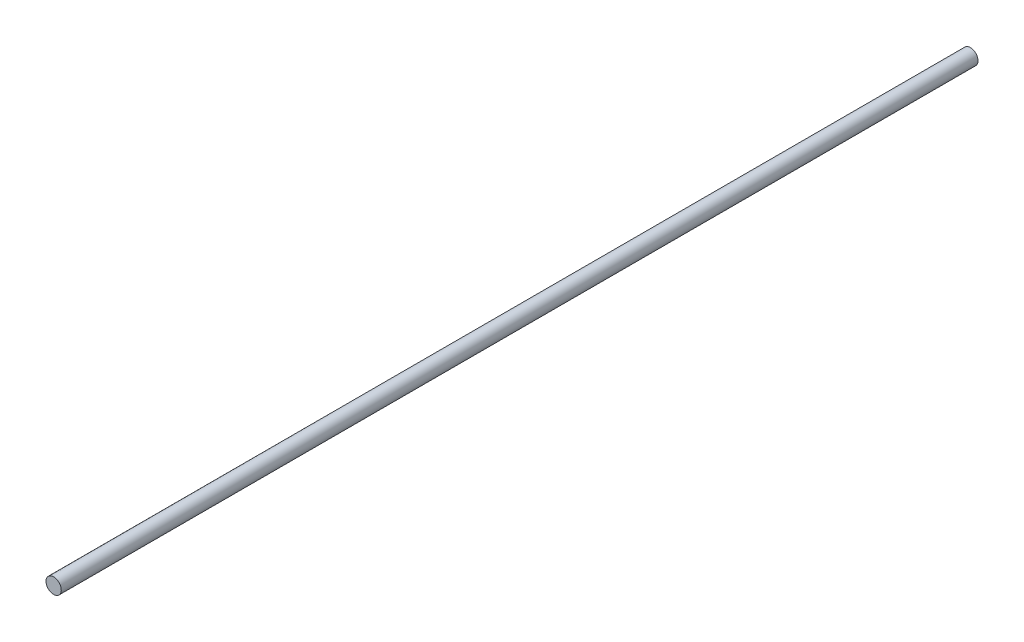
SolidWorks part; units mm, degrees
ref_plane "前视基准面" through (0, 0, 0) normal (0, 0, 1) x (1, 0, 0)
ref_plane "上视基准面" through (0, 0, 0) normal (0, 1, 0) x (1, 0, 0)
ref_plane "右视基准面" through (0, 0, 0) normal (1, 0, 0) x (0, 0, -1)
sketch "草图1" plane through (0, 0, 0) normal (0, 0, 1) x (1, 0, 0)
  circle A0 centre (0, 0) radius 5
  dimension "D1" = 10
extrude "拉伸1" add sketch "草图1" along normal blind 600
